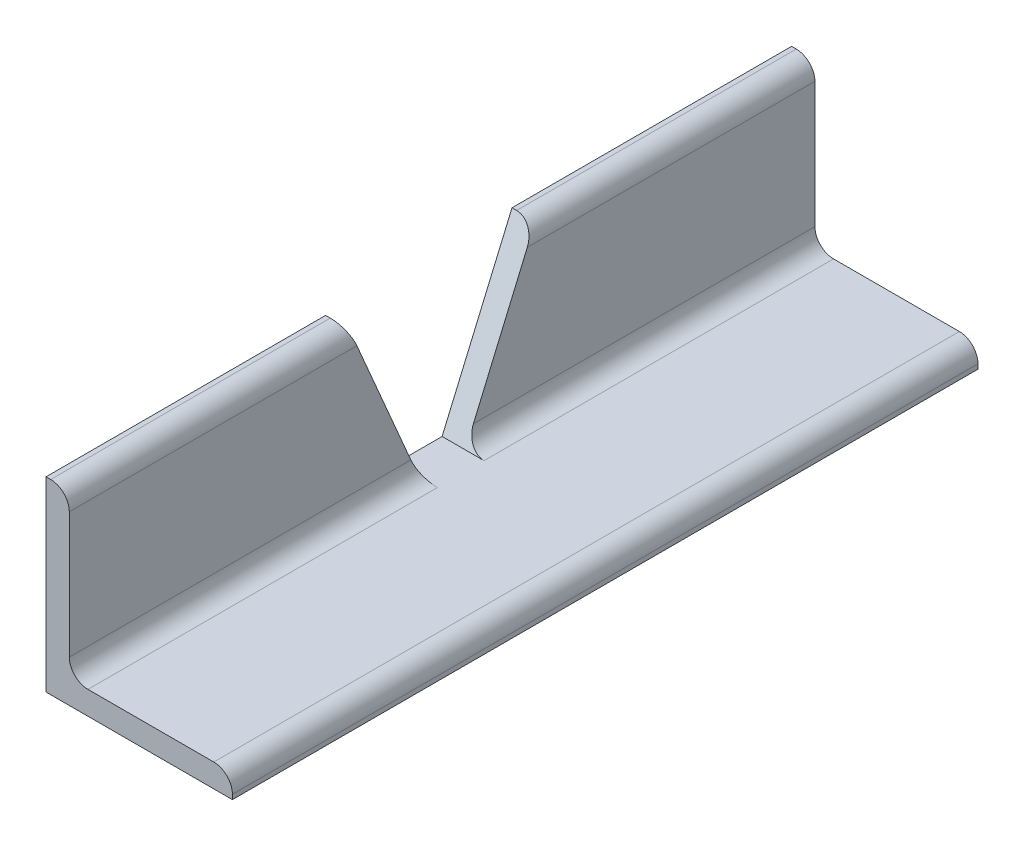
SolidWorks part; units mm, degrees
ref_plane "Front Plane" through (0, 0, 0) normal (0, 0, 1) x (1, 0, 0)
ref_plane "Top Plane" through (0, 0, 0) normal (0, 1, 0) x (1, 0, 0)
ref_plane "Right Plane" through (0, 0, 0) normal (1, 0, 0) x (0, 0, -1)
sketch "Sketch1" plane through (0, 0, 0) normal (0, 0, 1) x (1, 0, 0)
  line L0 (-12.7, 12.7) -> (-12.7, -12.7)
  line L1 (-12.7, -12.7) -> (12.7, -12.7)
  line L2 (-9.525, 10.16) -> (-9.525, -6.985)
  line L3 (-6.985, -9.525) -> (10.16, -9.525)
  line L4 (-12.065, 12.7) -> (-12.7, 12.7)
  line L5 (12.7, -12.7) -> (12.7, -12.065)
  line L6 (-9.525, -9.525) -> (12.7, -9.525) construction
  line L7 (-9.525, 12.7) -> (-9.525, -9.525) construction
  arc A0 (10.16, -9.525) -> (12.7, -12.065) centre (10.16, -12.065) cw
  arc A1 (-9.525, -6.985) -> (-6.985, -9.525) centre (-6.985, -6.985) ccw
  arc A2 (-9.525, 10.16) -> (-12.065, 12.7) centre (-12.065, 10.16) ccw
  point P2 (0, -12.7)
  point P17 (-12.7, 0)
  dimension "D4" = 2.54
  dimension "D1" = 25.4
  dimension "D2" = 25.4
  dimension "D3" = 3.175
extrude "Boss-Extrude1" add sketch "Sketch1" along normal mid plane 101.6
sketch "Sketch3" plane through (-12.7, 0, 0) normal (-1, 0, 0) x (0, 0, 1)
  line L0 (-50.8, -9.525) -> (50.8, -9.525) construction
  line L1 (-50.8, 12.7) -> (-50.8, -12.7) construction
  line L2 (50.8, 12.7) -> (50.8, -12.7) construction
  line L3 (50.8, -12.7) -> (-50.8, -12.7) construction
  line L4 (-12.7, 12.7) -> (-3.175, -9.525)
  line L5 (50.8, 12.7) -> (-50.8, 12.7) construction
  line L6 (-12.7, 12.7) -> (12.7, 12.7)
  line L7 (12.7, 12.7) -> (3.175, -9.525)
  line L8 (-3.175, -9.525) -> (3.175, -9.525)
  point P8 (0, -9.525)
  dimension "D1" = 3.175
  dimension "D2" = 25.4
  dimension "D3" = 6.35
extrude "Cut-Extrude1" cut sketch "Sketch3" against normal through all
